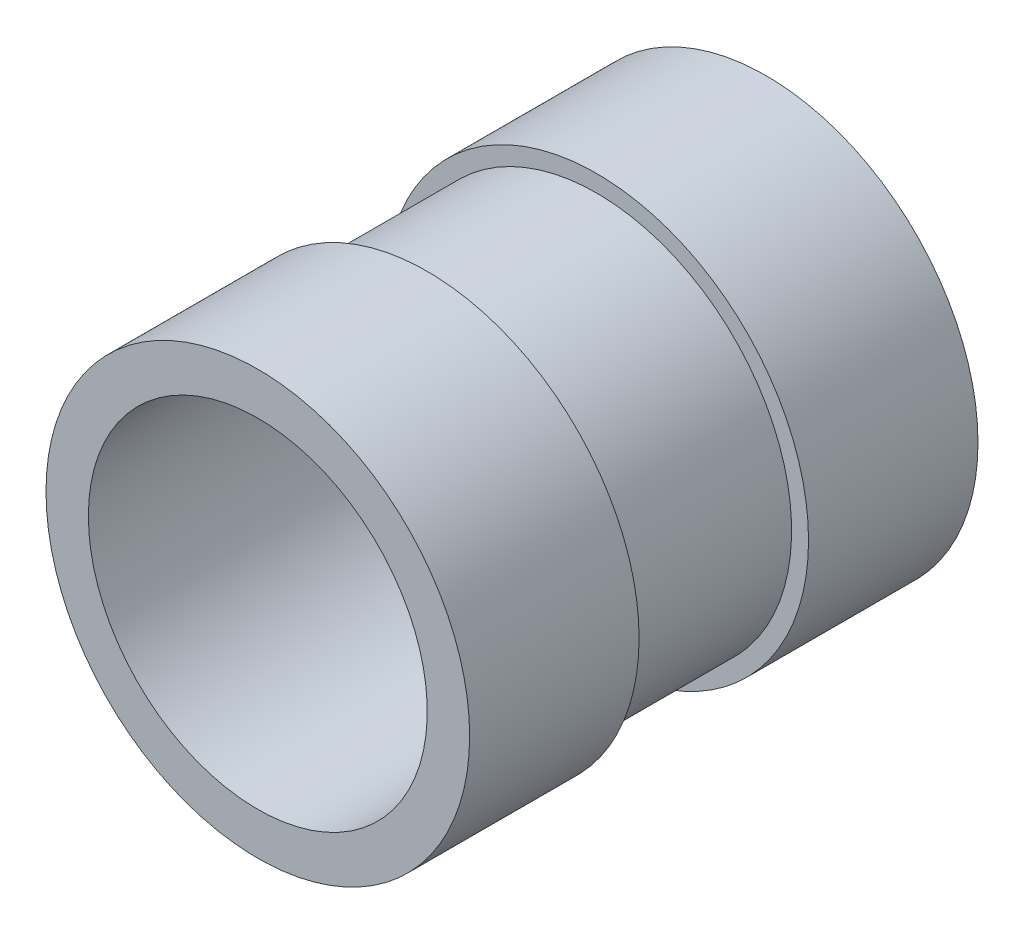
SolidWorks part; units mm, degrees
ref_plane "Front Plane" through (0, 0, 0) normal (0, 0, 1) x (1, 0, 0)
ref_plane "Top Plane" through (0, 0, 0) normal (0, 1, 0) x (1, 0, 0)
ref_plane "Right Plane" through (0, 0, 0) normal (1, 0, 0) x (0, 0, -1)
sketch "Sketch1" plane through (0, 0, 0) normal (0, 1, 0) x (1, 0, 0)
  line L0 (0, 0) -> (2.5, 0)
  line L1 (2.5, 0) -> (2.5, 2)
  line L2 (2.5, 2) -> (2.3, 2)
  line L3 (2.3, 2) -> (2.3, 4)
  line L4 (2.3, 4) -> (2.5, 4)
  line L5 (2.5, 4) -> (2.5, 6)
  line L6 (2.5, 6) -> (0, 6)
  line L7 (0, 6) -> (0, 0)
  line L8 (0, 11.944) -> (0, -8.2859) construction
  dimension "D1" = 6
  dimension "D2" = 2
  dimension "D3" = 2
  dimension "D4" = 0.2
  dimension "D5" = 2.5
revolve "Revolve1" add sketch "Sketch1" angle 360 about L8
sketch "Sketch2" plane through (0, 0, -6) normal (0, 0, -1) x (-1, 0, 0)
  circle A0 centre (0, 0) radius 2
  dimension "D1" = 4
extrude "Cut-Extrude1" cut sketch "Sketch2" against normal through all
